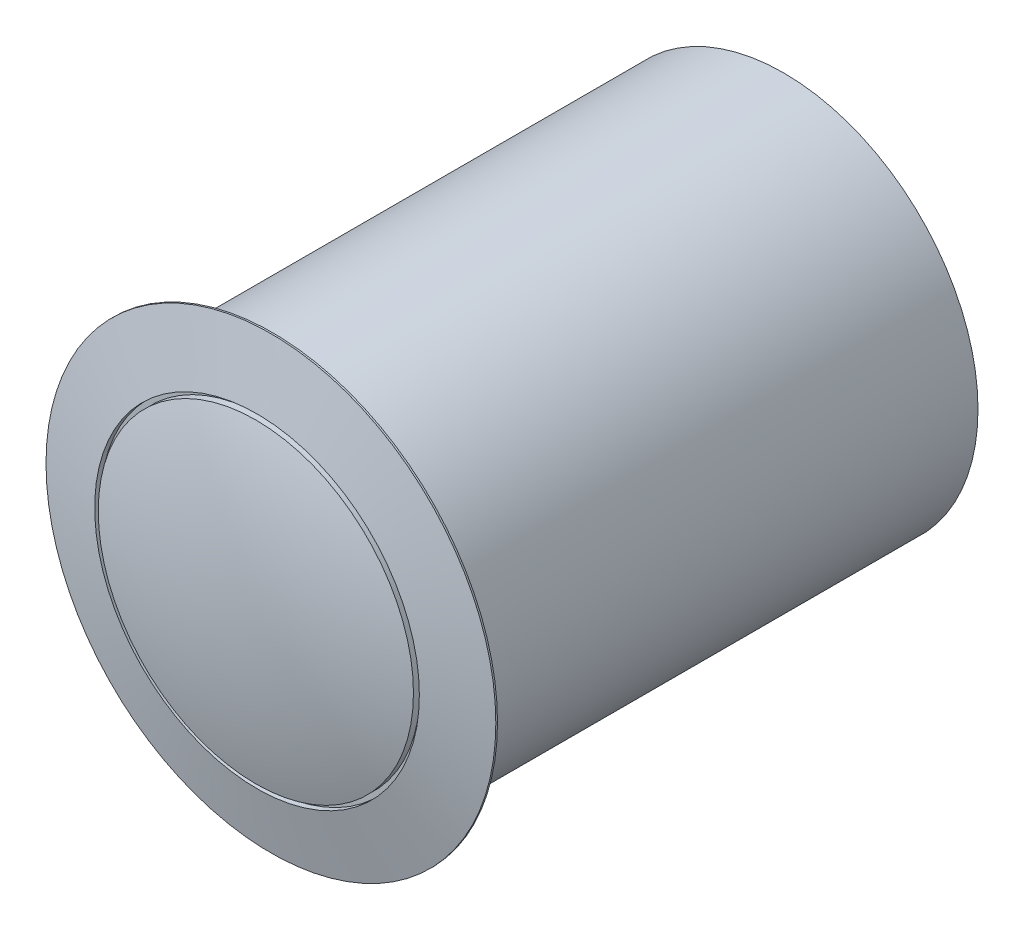
SolidWorks part; units mm, degrees
material "Chromovaná nerezová ocel"
ref_plane "Přední rovina" through (0, 0, 0) normal (0, 0, 1) x (1, 0, 0)
ref_plane "Horní rovina" through (0, 0, 0) normal (0, 1, 0) x (1, 0, 0)
ref_plane "Pravá rovina" through (0, 0, 0) normal (1, 0, 0) x (0, 0, -1)
sketch "Skica1" plane through (0, 0, 0) normal (0, 1, 0) x (1, 0, 0)
  line L0 (0, -3.3811) -> (0, 76.2406) construction
  line L1 (0, -1.9295) -> (13.0653, -1.9295) construction
  line L2 (9.5, 0) -> (9.5, 25)
  line L3 (7.9392, -0.7612) -> (11, -0.0821)
  line L4 (11, 0) -> (9.5, 0)
  line L5 (9.5, 25) -> (0, 25)
  line L6 (9.5, 0) -> (0, 0) construction
  line L7 (0, -1.9295) -> (0, 25)
  line L8 (7.9392, -0.7612) -> (7.9392, -0.4881)
  line L9 (7.9392, -0.4881) -> (7.7084, -0.4881)
  line L10 (7.7084, -0.4881) -> (7.7084, -0.8187)
  line L11 (11, 0) -> (11, -0.0821)
  arc A0 (0, -1.9295) -> (7.7084, -0.8187) centre (0, 25.3727) ccw
  dimension "D1" = 22
  dimension "D2" = 19
  dimension "D3" = 25
revolve "Rotovat1" add sketch "Skica1" angle 360 about L0
